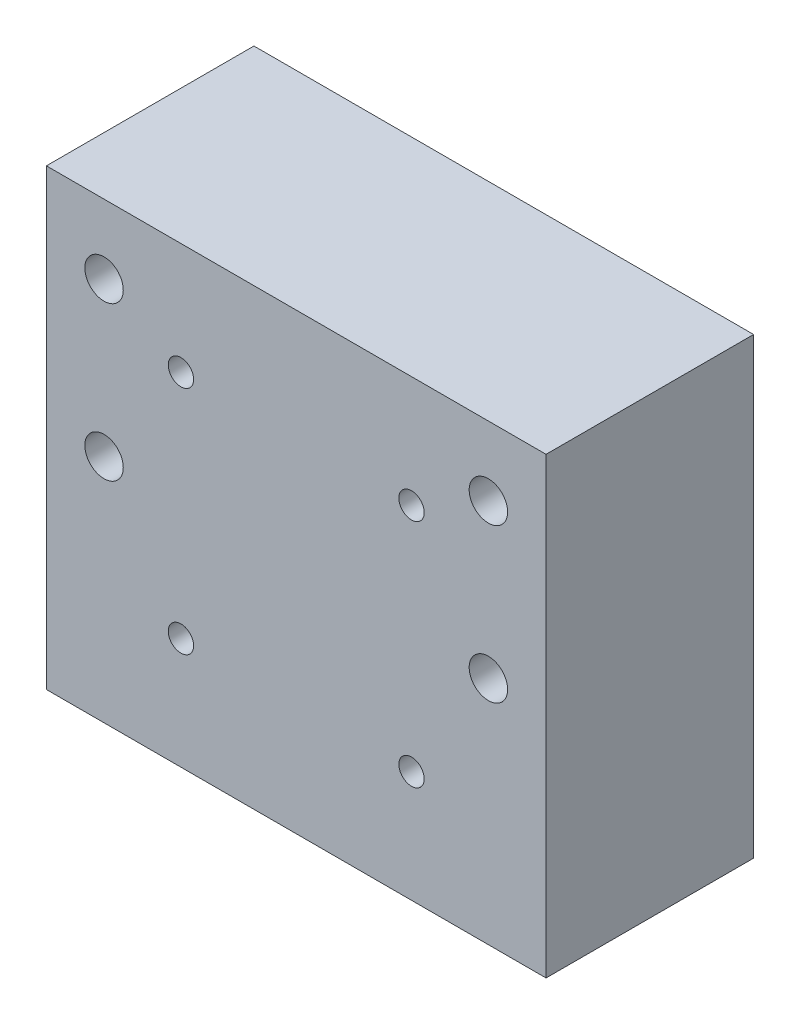
SolidWorks part; units mm, degrees
material "6061 Сплав"
ref_plane "Front" through (0, 0, 0) normal (0, 0, 1) x (1, 0, 0)
ref_plane "Top" through (0, 0, 0) normal (0, 1, 0) x (1, 0, 0)
ref_plane "Right" through (0, 0, 0) normal (1, 0, 0) x (0, 0, -1)
sketch "Эскиз1" plane through (0, 0, 0) normal (0, 0, 1) x (1, 0, 0)
  line L1 (-32.5, 29.5) -> (32.5, 29.5)
  line L2 (-32.5, 29.5) -> (-32.5, -29.5)
  line L3 (-32.5, -29.5) -> (32.5, -29.5)
  line L4 (32.5, 29.5) -> (32.5, -29.5)
  line L5 (-32.5, 29.5) -> (32.5, -29.5) construction
  line L6 (-32.5, -29.5) -> (32.5, 29.5) construction
  point P0 (0, 0)
  dimension "D1" = 65
  dimension "D2" = 59
extrude "Бобышка-Вытянуть1" add sketch "Эскиз1" along normal blind 27
sketch "Эскиз2" plane through (0, 0, 27) normal (0, 0, 1) x (1, 0, 0)
  line L0 (32.5, 29.5) -> (-32.5, 29.5) construction
  line L1 (-32.5, 29.5) -> (-32.5, -29.5) construction
  circle A0 centre (-25, 20.5) radius 2.5
  dimension "D1" = 9
  dimension "D2" = 7.5
extrude "Вырез-Вытянуть1" cut sketch "Эскиз2" against normal blind 27
pattern_linear "Линейный массив1" count 2 spacing 50 along (1, 0, 0) count 2 spacing 20 along (0, -1, 0) of "Вырез-Вытянуть1"
sketch "Эскиз3" plane through (0, 0, 27) normal (0, 0, 1) x (1, 0, 0)
  line L0 (-32.5, 29.5) -> (-32.5, -29.5) construction
  line L1 (32.5, 29.5) -> (-32.5, 29.5) construction
  circle A0 centre (-15, 15) radius 1.65
  dimension "D1" = 17.5
  dimension "D2" = 14.5
extrude "Вырез-Вытянуть2" cut sketch "Эскиз3" against normal blind 27
pattern_linear "Линейный массив2" count 2 spacing 30 along (1, 0, 0) count 2 spacing 30 along (0, -1, 0) of "Вырез-Вытянуть2"
